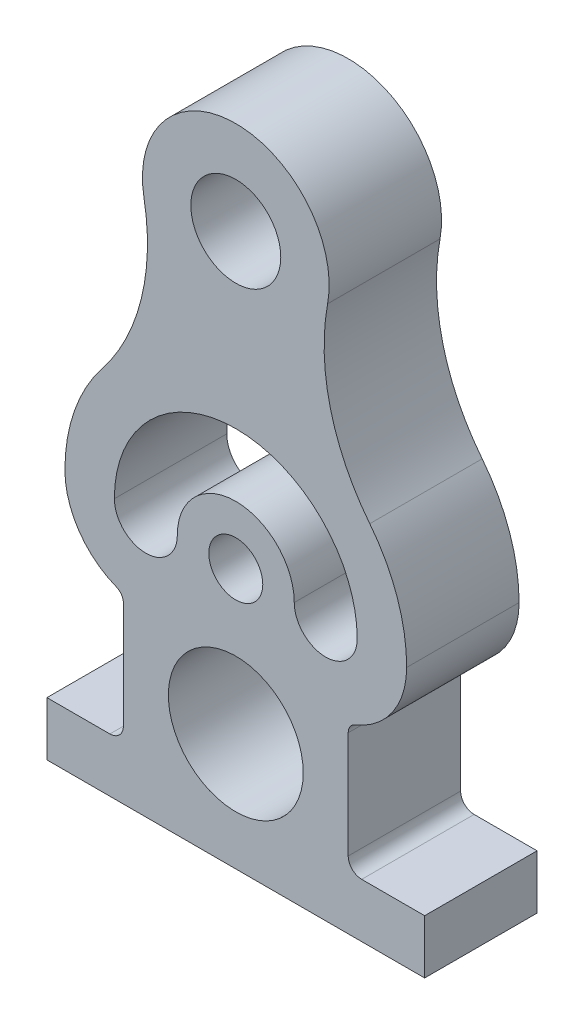
SolidWorks part; units mm, degrees
ref_plane "Front Plane" through (0, 0, 0) normal (0, 0, 1) x (1, 0, 0)
ref_plane "Top Plane" through (0, 0, 0) normal (0, 1, 0) x (1, 0, 0)
ref_plane "Right Plane" through (0, 0, 0) normal (1, 0, 0) x (0, 0, -1)
sketch "Sketch1" plane through (0, 0, 0) normal (0, 0, 1) x (1, 0, 0)
  line L0 (0, 0) -> (168, 0)
  line L1 (168, 0) -> (168, 24)
  line L2 (168, 24) -> (134, 24)
  line L3 (134, 24) -> (134, 81.0304)
  line L4 (0, 0) -> (0, 24)
  line L5 (0, 24) -> (34, 24)
  line L6 (34, 24) -> (34, 81.0304)
  circle A0 centre (84, 52) radius 30
  circle A1 centre (84, 115.6136) radius 12
  arc A2 (110, 115.6136) -> (58, 115.6136) centre (84, 115.6136) ccw
  arc A3 (138, 115.6136) -> (30, 115.6136) centre (84, 115.6136) ccw
  arc A5 (110, 115.6136) -> (138, 115.6136) centre (124, 115.6136) ccw
  arc A6 (30, 115.6136) -> (58, 115.6136) centre (44, 115.6136) ccw
  arc A7 (134, 81.0304) -> (160, 115.6136) centre (124, 115.6136) ccw
  arc A9 (8, 115.6136) -> (34, 81.0304) centre (44, 115.6136) ccw
  arc A10 (160, 115.6136) -> (143.589, 162.7851) centre (84, 115.6136) ccw
  circle A14 centre (84, 245.6136) radius 20
  arc A15 (124.8381, 238.1119) -> (43.1619, 238.1119) centre (84, 245.6136) ccw
  arc A16 (24.411, 162.7851) -> (43.1619, 238.1119) centre (-49.2912, 221.1288) ccw
  arc A17 (124.8381, 238.1119) -> (143.589, 162.7851) centre (217.2912, 221.1288) ccw
  arc A18 (24.411, 162.7851) -> (8, 115.6136) centre (84, 115.6136) ccw
  point P12 (84, 0)
  dimension "D6" = 60
  dimension "D8" = 24
  dimension "D10" = 52
  dimension "D11" = 108
  dimension "D12" = 40
  dimension "D9" = 28
  dimension "D13" = 72
  dimension "D14" = 130
  dimension "D15" = 188
  dimension "D16" = 188
  dimension "D1" = 168
  dimension "D2" = 24
  dimension "D3" = 34
  dimension "D4" = 24
  dimension "D5" = 34
  dimension "D7" = 52
extrude "Boss-Extrude1" add sketch "Sketch1" along normal blind 50
fillet "Fillet1" radius 6 2 edges at (34, 24, 25) (134, 24, 25)
fillet "Fillet2" radius 5 2 edges at (34, 81.0304, 25) (134, 81.0304, 25)
